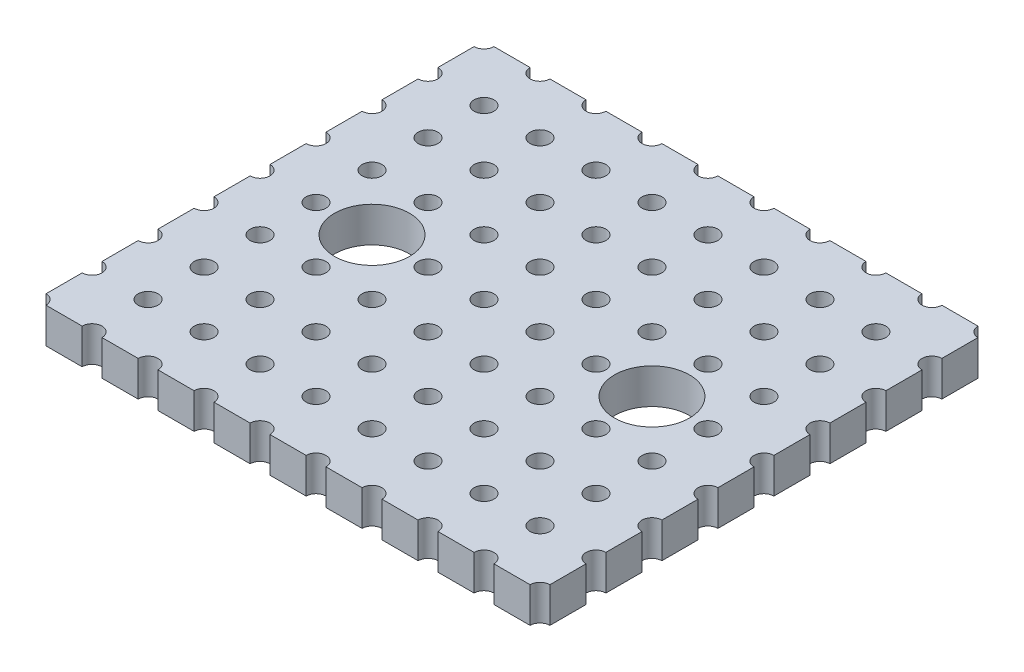
SolidWorks part; units mm, degrees
ref_plane "Plan de face" through (0, 0, 0) normal (0, 0, 1) x (1, 0, 0)
ref_plane "Plan de dessus" through (0, 0, 0) normal (0, 1, 0) x (1, 0, 0)
ref_plane "Plan de droite" through (0, 0, 0) normal (1, 0, 0) x (0, 0, -1)
sketch "Esquisse1" plane through (0, 0, 0) normal (0, 1, 0) x (1, 0, 0)
  line L1 (-3.8847, 3.5299) -> (18.9753, 3.5299)
  line L2 (-3.8847, 3.5299) -> (-3.8847, -16.7901)
  line L3 (-3.8847, -16.7901) -> (18.9753, -16.7901)
  line L4 (18.9753, 3.5299) -> (18.9753, -16.7901)
  dimension "D1" = 22.86
  dimension "D2" = 20.32
extrude "Boss.-Extru.1" add sketch "Esquisse1" along normal blind 1.6
sketch "Esquisse2" plane through (0, 1.6, 0) normal (0, 1, 0) x (1, 0, 0)
  circle A0 centre (-3.8847, 3.5299) radius 0.45
  circle A1 centre (-1.3447, 3.5299) radius 0.45
  circle A2 centre (1.1953, 3.5299) radius 0.45
  circle A3 centre (3.7353, 3.5299) radius 0.45
  circle A4 centre (-1.3447, 0.9899) radius 0.45
  circle A5 centre (1.1953, 0.9899) radius 0.45
  circle A6 centre (3.7353, 0.9899) radius 0.45
  circle A7 centre (-1.3447, -1.5501) radius 0.45
  circle A8 centre (1.1953, -1.5501) radius 0.45
  circle A9 centre (3.7353, -1.5501) radius 0.45
  circle A10 centre (-1.3447, -4.0901) radius 0.45
  circle A11 centre (1.1953, -4.0901) radius 0.45
  circle A12 centre (3.7353, -4.0901) radius 0.45
  circle A13 centre (-1.3447, -6.6301) radius 0.45
  circle A14 centre (1.1953, -6.6301) radius 0.45
  circle A15 centre (3.7353, -6.6301) radius 0.45
  circle A16 centre (-1.3447, -9.1701) radius 0.45
  circle A17 centre (1.1953, -9.1701) radius 0.45
  circle A18 centre (3.7353, -9.1701) radius 0.45
  circle A19 centre (-1.3447, -11.7101) radius 0.45
  circle A20 centre (1.1953, -11.7101) radius 0.45
  circle A21 centre (3.7353, -11.7101) radius 0.45
  circle A22 centre (-1.3447, -14.2501) radius 0.45
  circle A23 centre (1.1953, -14.2501) radius 0.45
  circle A24 centre (3.7353, -14.2501) radius 0.45
  circle A25 centre (-3.8847, 0.9899) radius 0.45
  circle A26 centre (-3.8847, -1.5501) radius 0.45
  circle A27 centre (-3.8847, -4.0901) radius 0.45
  circle A28 centre (-3.8847, -6.6301) radius 0.45
  circle A29 centre (-3.8847, -9.1701) radius 0.45
  circle A30 centre (-3.8847, -11.7101) radius 0.45
  circle A31 centre (-3.8847, -14.2501) radius 0.45
  circle A32 centre (6.2753, 3.5299) radius 0.45
  circle A33 centre (6.2753, 0.9899) radius 0.45
  circle A34 centre (6.2753, -1.5501) radius 0.45
  circle A35 centre (6.2753, -4.0901) radius 0.45
  circle A36 centre (6.2753, -6.6301) radius 0.45
  circle A37 centre (6.2753, -9.1701) radius 0.45
  circle A38 centre (6.2753, -11.7101) radius 0.45
  circle A39 centre (6.2753, -14.2501) radius 0.45
  circle A40 centre (-3.8847, -16.7901) radius 0.45
  circle A41 centre (-1.3447, -16.7901) radius 0.45
  circle A42 centre (1.1953, -16.7901) radius 0.45
  circle A43 centre (3.7353, -16.7901) radius 0.45
  circle A44 centre (6.2753, -16.7901) radius 0.45
  circle A55 centre (8.8153, 3.5299) radius 0.45
  circle A56 centre (11.3553, 3.5299) radius 0.45
  circle A57 centre (13.8953, 3.5299) radius 0.45
  circle A58 centre (16.4353, 3.5299) radius 0.45
  circle A59 centre (18.9753, 3.5299) radius 0.45
  circle A60 centre (8.8153, 0.9899) radius 0.45
  circle A61 centre (11.3553, 0.9899) radius 0.45
  circle A62 centre (13.8953, 0.9899) radius 0.45
  circle A63 centre (16.4353, 0.9899) radius 0.45
  circle A64 centre (18.9753, 0.9899) radius 0.45
  circle A65 centre (8.8153, -1.5501) radius 0.45
  circle A66 centre (11.3553, -1.5501) radius 0.45
  circle A67 centre (13.8953, -1.5501) radius 0.45
  circle A68 centre (16.4353, -1.5501) radius 0.45
  circle A69 centre (18.9753, -1.5501) radius 0.45
  circle A70 centre (8.8153, -4.0901) radius 0.45
  circle A71 centre (11.3553, -4.0901) radius 0.45
  circle A72 centre (13.8953, -4.0901) radius 0.45
  circle A73 centre (16.4353, -4.0901) radius 0.45
  circle A74 centre (18.9753, -4.0901) radius 0.45
  circle A75 centre (8.8153, -6.6301) radius 0.45
  circle A76 centre (11.3553, -6.6301) radius 0.45
  circle A77 centre (13.8953, -6.6301) radius 0.45
  circle A78 centre (16.4353, -6.6301) radius 0.45
  circle A79 centre (18.9753, -6.6301) radius 0.45
  circle A80 centre (8.8153, -9.1701) radius 0.45
  circle A81 centre (11.3553, -9.1701) radius 0.45
  circle A82 centre (13.8953, -9.1701) radius 0.45
  circle A83 centre (16.4353, -9.1701) radius 0.45
  circle A84 centre (18.9753, -9.1701) radius 0.45
  circle A85 centre (8.8153, -11.7101) radius 0.45
  circle A86 centre (11.3553, -11.7101) radius 0.45
  circle A87 centre (13.8953, -11.7101) radius 0.45
  circle A88 centre (16.4353, -11.7101) radius 0.45
  circle A89 centre (18.9753, -11.7101) radius 0.45
  circle A90 centre (8.8153, -14.2501) radius 0.45
  circle A91 centre (11.3553, -14.2501) radius 0.45
  circle A92 centre (13.8953, -14.2501) radius 0.45
  circle A93 centre (16.4353, -14.2501) radius 0.45
  circle A94 centre (18.9753, -14.2501) radius 0.45
  circle A95 centre (8.8153, -16.7901) radius 0.45
  circle A96 centre (11.3553, -16.7901) radius 0.45
  circle A97 centre (13.8953, -16.7901) radius 0.45
  circle A98 centre (16.4353, -16.7901) radius 0.45
  circle A99 centre (18.9753, -16.7901) radius 0.45
  dimension "D1" = 0.9
  dimension "D4" = 10
  dimension "D5" = 9
extrude "Enlèv. mat.-Extru.1" cut sketch "Esquisse2" against normal through all
hole_wizard "Dégagement M31" positions "Esquisse3" profile "Esquisse4" hole size "M3" standard "ISO" end condition through all
sketch "Esquisse3" plane through (0, 1.6, 0) normal (0, 1, 0) x (1, 0, 0)
  circle A1 centre (1.1953, -6.6301) radius 0.45 construction
  circle A3 centre (13.8953, -6.6301) radius 0.45 construction
  point P0 (13.8953, -6.6301)
  point P8 (1.1953, -6.6301)
sketch "Esquisse4" plane through (13.8953, 1.6, 6.6301) normal (1, 0, 0) x (0, 0, 1)
  line L0 (0, 0) -> (0, 1.6)
  line L1 (0, 1.6) -> (1.7, 1.6)
  line L2 (1.7, 1.6) -> (1.7, 0)
  line L5 (1.7, 0) -> (0, 0)
  line L11 (0, -6.35) -> (0, 107.95) construction
  dimension "Diamètre du perçage jusqu'au prochain" = 3.4
  dimension "Profondeur du perçage jusqu'au prochain" = 1.6
